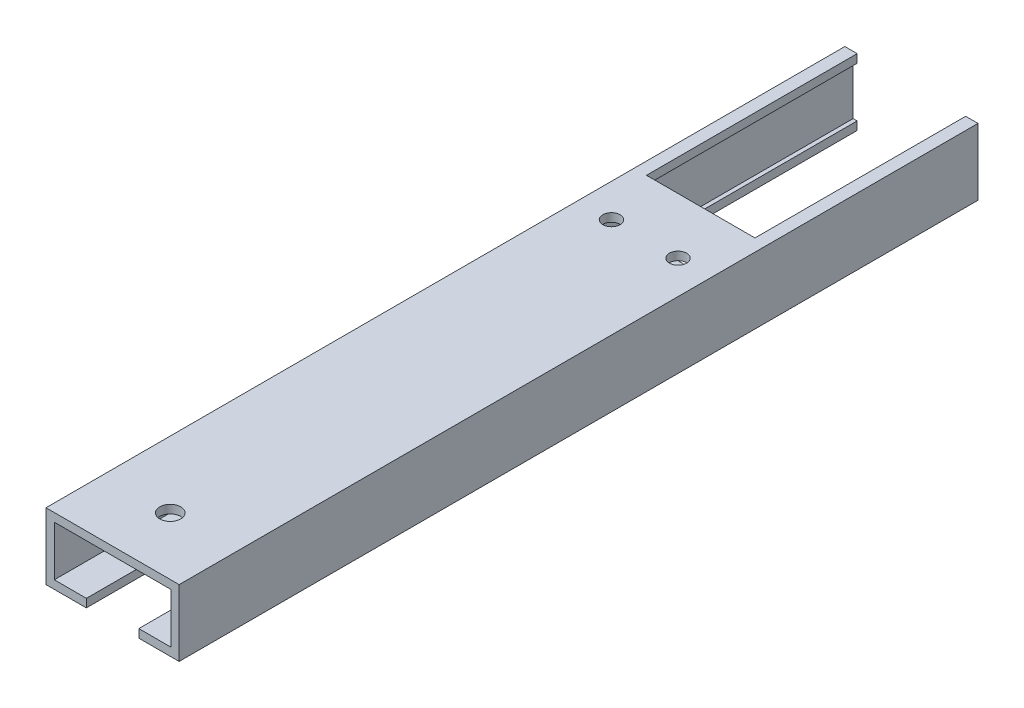
SolidWorks part; units mm, degrees
material "6061 Alloy"
ref_plane "Front Plane" through (0, 0, 0) normal (0, 0, 1) x (1, 0, 0)
ref_plane "Top Plane" through (0, 0, 0) normal (0, 1, 0) x (1, 0, 0)
ref_plane "Right Plane" through (0, 0, 0) normal (1, 0, 0) x (0, 0, -1)
sketch "Sketch1" plane through (0, 0, 0) normal (0, 0, 1) x (1, 0, 0)
  line L0 (-11.1125, 4.7625) -> (11.1125, 4.7625)
  line L2 (-12.7, 6.35) -> (12.7, 6.35)
  line L3 (-12.7, 6.35) -> (-12.7, -6.35)
  line L4 (-12.7, -6.35) -> (12.7, -6.35)
  line L5 (12.7, 6.35) -> (12.7, -6.35)
  line L10 (11.1125, 4.7625) -> (11.1125, -4.7625)
  line L11 (-11.1125, -4.7625) -> (11.1125, -4.7625)
  line L12 (-11.1125, 4.7625) -> (-11.1125, -4.7625)
  point P12 (0, 6.35)
  point P14 (12.7, 0)
  dimension "Wall Thickness" = 1.5875
  dimension "Outside Width" = 25.4
  dimension "Outside Height" = 12.7
  dimension "Inside Height" = 9.525
  dimension "Inside Width" = 22.225
sketch "Sketch2" plane through (0, 0, 0) normal (1, 0, 0) x (0, 0, -1)
  line L0 (304.8, 0) -> (-304.8, 0)
  point P4 (0, 0)
  point P7 (-304.8, 0)
  point P10 (304.8, 0)
  dimension "Length" = 609.6
sketch "Sketch3" plane through (0, 0, 0) normal (0, 0, 1) x (1, 0, 0)
  line L21 (12.7, 6.35) -> (-12.7, 6.35)
  line L22 (12.7, -6.35) -> (12.7, 6.35)
  line L23 (-12.7, -6.35) -> (12.7, -6.35)
  line L24 (-12.7, 6.35) -> (-12.7, -6.35)
  line L25 (12.7, 6.35) -> (-12.7, 6.35)
  line L26 (12.7, -6.35) -> (12.7, 6.35)
  line L27 (-12.7, -6.35) -> (12.7, -6.35)
  line L28 (-12.7, 6.35) -> (-12.7, -6.35)
  line L29 (11.1125, 4.7625) -> (-11.1125, 4.7625)
  line L30 (11.1125, -4.7625) -> (11.1125, 4.7625)
  line L31 (-11.1125, -4.7625) -> (11.1125, -4.7625)
  line L32 (-11.1125, 4.7625) -> (-11.1125, -4.7625)
  line L33 (11.1125, 4.7625) -> (-11.1125, 4.7625)
  line L34 (11.1125, -4.7625) -> (11.1125, 4.7625)
  line L35 (-11.1125, -4.7625) -> (11.1125, -4.7625)
  line L36 (-11.1125, 4.7625) -> (-11.1125, -4.7625)
  dimension "D1" = 0
  dimension "D2" = 0
extrude "Boss-Extrude1" add sketch "Sketch3" along normal blind 152.4
sketch "Drawing Reference" plane through (0, 0, 0) normal (1, 0, 0) x (0, 0, -1)
  line L0 (-304.8, 0) -> (304.8, 0) construction
  line L1 (-76.2, -6.35) -> (-76.2, 6.35) construction
  line L2 (-152.4, -6.35) -> (0, -6.35) construction
  line L5 (-152.4, 6.35) -> (0, 6.35) construction
  point P7 (-286.512, 0)
  point P8 (134.112, 0)
  dimension "D1" = 18.288
sketch "Sketch4" plane through (0, 6.35, 0) normal (0, 1, 0) x (1, 0, 0)
  line L0 (12.7, -152.4) -> (-12.7, -152.4) construction
  line L1 (-12.7, -152.4) -> (-12.7, 0) construction
  circle A0 centre (0, -141.4) radius 2
  dimension "D1" = 4
  dimension "D2" = 11
  dimension "D3" = 12.7
extrude "Cut-Extrude1" cut sketch "Sketch4" against normal up to surface (1.5875 mm away) up to face at (0, 4.7625, 76.2)
sketch "Sketch5" plane through (0, -6.35, 0) normal (0, -1, 0) x (1, 0, 0)
  circle A1 centre (-8, 141.4) radius 1.5004
  circle A2 centre (0, 149.4) radius 1.5004
  circle A3 centre (8, 141.4) radius 1.5004
  point P12 (0, 141.4)
extrude "Cut-Extrude2" cut sketch "Sketch5" against normal up to surface (1.5875 mm away) up to face at (0, -4.7625, 76.2)
sketch "Sketch6" plane through (0, -6.35, 0) normal (0, -1, 0) x (1, 0, 0)
  line L0 (-5, 152.4) -> (-5, 136.4)
  line L1 (-12.7, 152.4) -> (12.7, 152.4) construction
  line L2 (-5, 136.4) -> (5, 136.4)
  line L3 (5, 136.4) -> (5, 152.4)
  line L4 (-8, 141.4) -> (8, 141.4) construction
  line L5 (0, 149.4) -> (0, 127.1732) construction
  circle A0 centre (-8, 141.4) radius 1.5004 construction
  circle A1 centre (8, 141.4) radius 1.5004 construction
  circle A3 centre (0, 141.4) radius 5 construction
  point P18 (0, 141.4)
  dimension "D1" = 10
extrude "Cut-Extrude3" cut sketch "Sketch6" against normal blind 2.54 and the other way through all
sketch "Sketch7" plane through (0, -6.35, 0) normal (0, -1, 0) x (1, 0, 0)
  line L1 (-12.7, 152.4) -> (-12.7, 0) construction
  line L7 (0, 0) -> (0, 56.8534) construction
  line L8 (-12.7, 0) -> (12.7, 0) construction
  line L10 (-10.35, 40.2) -> (10.35, 40.2)
  line L11 (-10.35, 40.2) -> (-10.35, 0)
  line L12 (-10.35, 0) -> (10.35, 0)
  line L13 (10.35, 40.2) -> (10.35, 0)
  line L14 (-10.35, 40.2) -> (10.35, 0) construction
  line L15 (-10.35, 0) -> (10.35, 40.2) construction
  point P4 (0, 20.1)
  dimension "D1" = 20.7
  dimension "D2" = 40.2
  dimension "D3" = 2.35
extrude "Cut-Extrude4" cut sketch "Sketch7" against normal through all
sketch "Sketch8" plane through (0, -6.35, 0) normal (0, -1, 0) x (1, 0, 0)
  line L0 (10.35, 40.2) -> (-10.35, 40.2) construction
  line L1 (-12.7, 152.4) -> (-12.7, 0) construction
  point P0 (-6.35, 50.875)
  point P1 (6.35, 50.875)
  dimension "D1" = 10.675
  dimension "D2" = 6.35
  dimension "D3" = 12.7
hole_wizard "M4x0.7 Tapped Hole1" positions "Sketch9" profile "Sketch10" tap size "M4x0.7" standard "ANSI Metric" end condition through all
sketch "Sketch9" plane through (0, -6.35, 0) normal (0, -1, 0) x (-1, 0, 0)
  point P0 (-6.35, -50.875)
  point P3 (6.35, -50.875)
sketch "Sketch10" plane through (6.35, -6.35, 50.875) normal (1, 0, 0) x (0, 0, -1)
  line L0 (0, 0) -> (0, 12.7)
  line L1 (0, 12.7) -> (1.65, 12.7)
  line L2 (1.65, 12.7) -> (1.65, 0)
  line L5 (1.65, 0) -> (0, 0)
  line L11 (0, -6.35) -> (0, 107.95) construction
  dimension "Thru Tap Drill Dia." = 3.3
  dimension "Thru Tap Drill Depth" = 12.7
equation "\"D1@Drawing Reference\"=\"Outside Width@Sketch1\" * 0.72"
